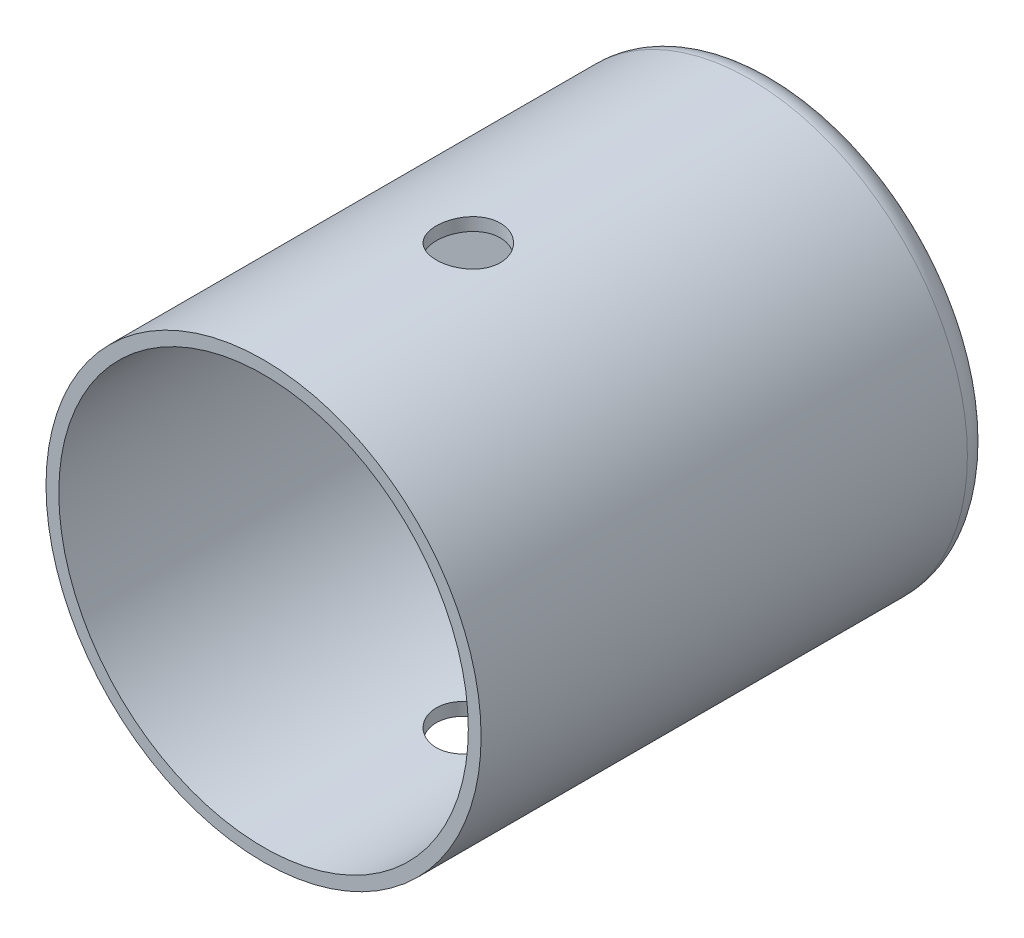
SolidWorks part; units mm, degrees
ref_plane "Front Plane" through (0, 0, 0) normal (0, 0, 1) x (1, 0, 0)
ref_plane "Top Plane" through (0, 0, 0) normal (0, 1, 0) x (1, 0, 0)
ref_plane "Right Plane" through (0, 0, 0) normal (1, 0, 0) x (0, 0, -1)
sketch "Sketch1" plane through (0, 0, 0) normal (0, 0, 1) x (1, 0, 0)
  circle A0 centre (0, 0) radius 17
  dimension "D1" = 34
extrude "Boss-Extrude1" add sketch "Sketch1" along normal blind 12
sketch "Sketch2" plane through (0, 0, 12) normal (0, 0, 1) x (1, 0, 0)
  circle A0 centre (0, 0) radius 16
  circle M1 centre (0, 0) radius 17
  dimension "D1" = 32
extrude "Boss-Extrude2" add sketch "Sketch2" along normal blind 28 contours A0 M1
sketch "Sketch3" plane through (0, 0, 0) normal (0, 1, 0) x (1, 0, 0)
  circle A0 centre (0, -24) radius 2.5
  dimension "D2" = 5
  dimension "D1" = 24
extrude "Cut-Extrude1" cut sketch "Sketch3" against normal through all both and the other way through all
fillet "Fillet1" radius 2 1 edges at (17, 0, 0)
